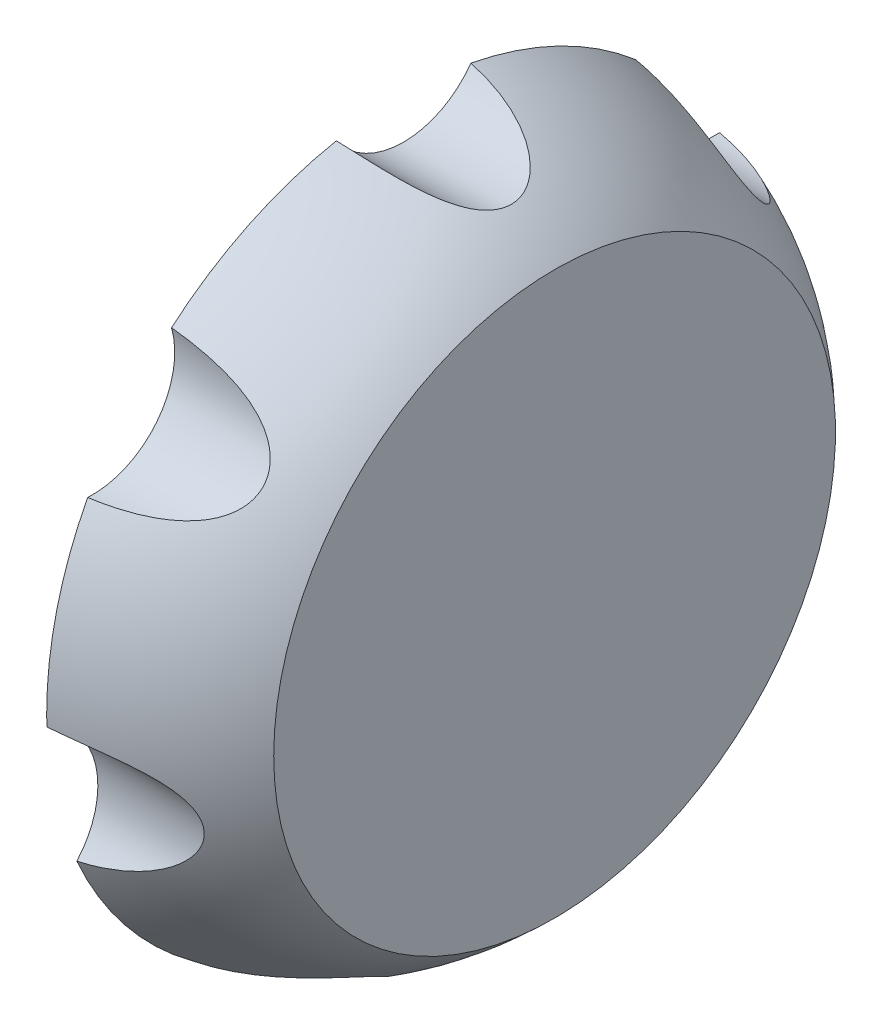
SolidWorks part; units mm, degrees
ref_plane "Front Plane" through (0, 0, 0) normal (0, 0, 1) x (1, 0, 0)
ref_plane "Top Plane" through (0, 0, 0) normal (0, 1, 0) x (1, 0, 0)
ref_plane "Right Plane" through (0, 0, 0) normal (1, 0, 0) x (0, 0, -1)
sketch "Sketch1" plane through (0, 0, 0) normal (0, 0, 1) x (1, 0, 0)
  line L2 (0, 38.1) -> (50.8, 38.1)
  line L3 (50.8, 38.1) -> (50.8, 0)
  line L4 (50.8, 0) -> (69.85, 0)
  line L5 (69.85, 0) -> (69.85, 129.9349)
  line L6 (0, 38.1) -> (0, 165.1)
  arc A0 (0, 165.1) -> (69.85, 129.9349) centre (-19.4087, 39.5918) cw
  dimension "D5" = 127
  dimension "D1" = 38.1
  dimension "D2" = 50.8
  dimension "D3" = 19.05
  dimension "D4" = 127
  dimension "D6" = 19.4087
revolve "Revolve1" add sketch "Sketch1" angle 360 about L4
sketch "Sketch3" plane through (69.85, 0, 0) normal (1, 0, 0) x (0, 0, -1)
  circle A1 centre (0, 184.15) radius 38.1
  circle A2 centre (143.9743, 114.8156) radius 38.1
  circle A3 centre (179.533, -40.9772) radius 38.1
  circle A4 centre (79.8997, -165.9134) radius 38.1
  circle A5 centre (-79.8997, -165.9134) radius 38.1
  circle A6 centre (-179.533, -40.9772) radius 38.1
  circle A7 centre (-143.9743, 114.8156) radius 38.1
  point P20 (0, 0)
  dimension "D2" = 76.2
  dimension "D3" = 7
extrude "Cut-Extrude1" cut sketch "Sketch3" against normal up to surface (69.85 mm away) up to face at (0, 0, 38.1)
